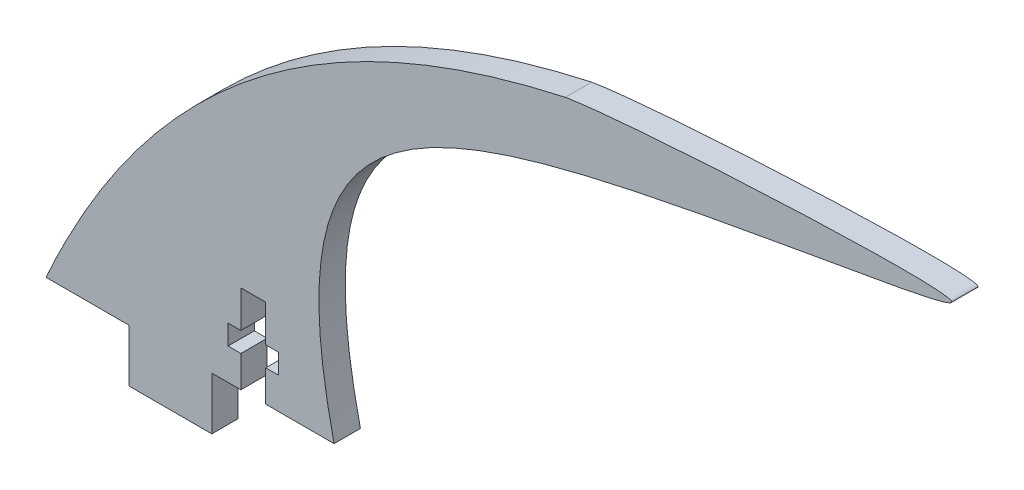
SolidWorks part; units mm, degrees
ref_plane "前视基准面" through (0, 0, 0) normal (0, 0, 1) x (1, 0, 0)
ref_plane "上视基准面" through (0, 0, 0) normal (0, 1, 0) x (1, 0, 0)
ref_plane "右视基准面" through (0, 0, 0) normal (1, 0, 0) x (0, 0, -1)
sketch "Sketch1" plane through (0, 0, 0) normal (0, 0, 1) x (1, 0, 0)
  line L0 (-360, 0) -> (360, 0) construction
  line L1 (-19.5671, 50.1455) -> (753.6757, 55.0373) construction
  line L2 (-32.114, 89.2833) -> (541.2194, 89.2833) construction
sketch "Sketch2" plane through (0, 0, 0) normal (0, 0, 1) x (1, 0, 0)
  line L0 (-171.469, -33.2992) -> (-136.7224, -33.2992)
  spline S0 degree 3 poles (-108.8379, 16.8217) (-99.6698, 18.3068) (-32.5492, 21.4731) (-123.0126, 9.7305) (-143.4843, -3.9021) (-136.7224, -33.2992) knots 0 0 0 0 0.306498 0.587228 1 1 1 1
  spline S8 degree 3 poles (-108.8379, 16.8217) (-134.7274, 11.1332) (-157.4561, -2.0821) (-171.469, -33.2992) knots 0.52731 0.52731 0.52731 0.52731 1 1 1 1
extrude "Boss-Extrude1" add sketch "Sketch2" along normal blind 3.175
sketch "Sketch3" plane through (0, 0, 3.175) normal (0, 0, 1) x (1, 0, 0)
  line L0 (-156.469, -23.0187) -> (-156.469, -49.8356) construction
  line L1 (-161.469, -33.2992) -> (-151.469, -33.2992)
  line L2 (-171.469, -33.2992) -> (-136.7224, -33.2992) construction
  line L3 (-161.469, -33.2992) -> (-161.469, -39.6492)
  line L4 (-161.469, -39.6492) -> (-151.469, -39.6492)
  line L5 (-151.469, -39.6492) -> (-151.469, -33.2992)
  point P6 (-156.469, -33.2992)
  dimension "D1" = 10
  dimension "D2" = 15
  dimension "D3" = 6.35
extrude "Boss-Extrude2" add sketch "Sketch3" against normal blind 3.175
sketch "Sketch5" plane through (0, 0, 3.175) normal (0, 0, 1) x (1, 0, 0)
  line L0 (-146.469, -4.9545) -> (-146.469, -56.9042) construction
  line L1 (-147.969, -33.2992) -> (-144.969, -33.2992)
  line L2 (-151.469, -33.2992) -> (-136.7224, -33.2992) construction
  line L3 (-147.969, -33.2992) -> (-147.969, -29.4992)
  line L4 (-147.969, -22.6492) -> (-144.969, -22.6492)
  line L5 (-144.969, -22.6492) -> (-144.969, -27.0992)
  line L6 (-161.469, -39.6492) -> (-151.469, -39.6492) construction
  line L7 (-143.419, -27.0992) -> (-143.419, -29.4992)
  line L8 (-149.519, -27.0992) -> (-149.519, -29.4992)
  line L9 (-149.519, -27.0992) -> (-147.969, -27.0992)
  line L10 (-149.519, -29.4992) -> (-147.969, -29.4992)
  line L11 (-149.519, -28.2992) -> (-93.8427, -28.2992) construction
  line L12 (-161.469, -33.2992) -> (-161.469, -39.6492) construction
  line L13 (-144.969, -27.0992) -> (-143.419, -27.0992)
  line L14 (-144.969, -29.4992) -> (-143.419, -29.4992)
  line L15 (-147.969, -27.0992) -> (-147.969, -22.6492)
  line L16 (-144.969, -29.4992) -> (-144.969, -33.2992)
  point P6 (-146.469, -33.2992)
  dimension "D1" = 3
  dimension "D2" = 17
  dimension "D3" = 6.1
  dimension "D4" = 5
  dimension "D5" = 15
  dimension "D6" = 2.4
extrude "Cut-Extrude2" cut sketch "Sketch5" against normal through all
